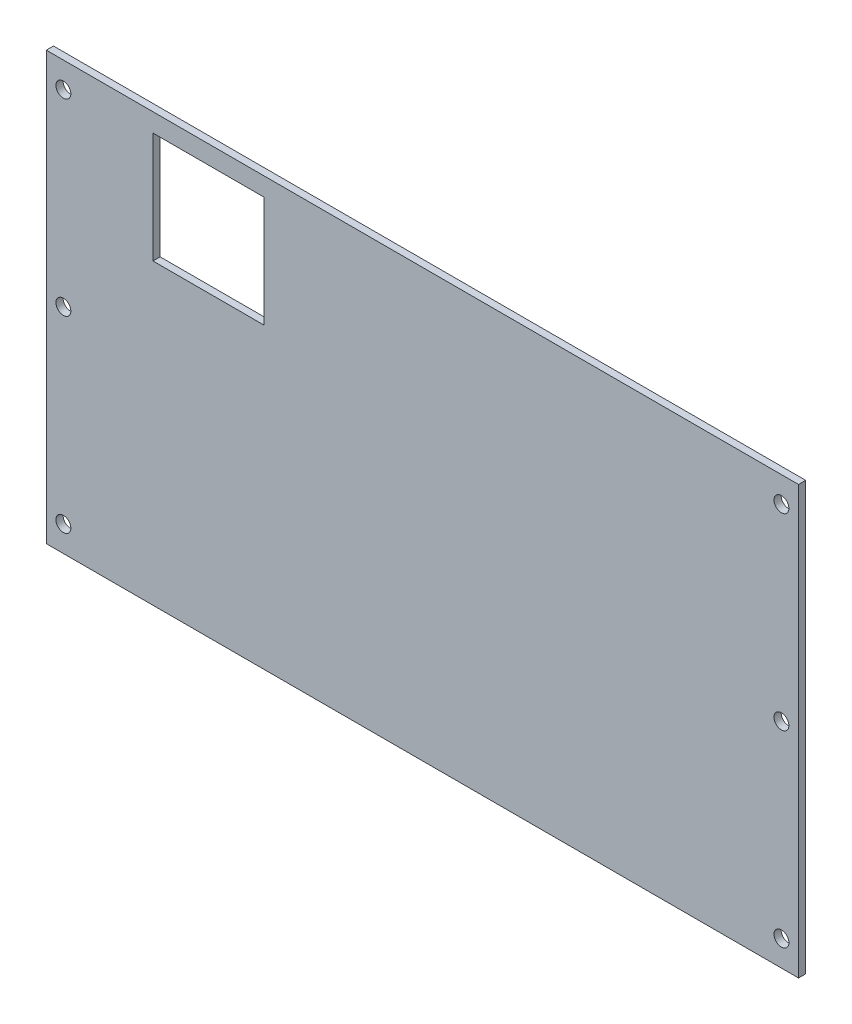
SolidWorks part; units mm, degrees
ref_plane "Front Plane" through (0, 0, 0) normal (0, 0, 1) x (1, 0, 0)
ref_plane "Top Plane" through (0, 0, 0) normal (0, 1, 0) x (1, 0, 0)
ref_plane "Right Plane" through (0, 0, 0) normal (1, 0, 0) x (0, 0, -1)
sketch "Sketch1" plane through (0, 0, 0) normal (0, 0, 1) x (1, 0, 0)
  line L1 (0, 0) -> (279.4, 0)
  line L2 (0, 0) -> (0, 158.75)
  line L3 (0, 158.75) -> (279.4, 158.75)
  line L4 (279.4, 0) -> (279.4, 158.75)
extrude "Boss-Extrude1" add sketch "Sketch1" along normal blind 2.667
sketch "Sketch2" plane through (0, 0, 0) normal (0, 0, 1) x (1, 0, 0)
  line L1 (39.624, 110.744) -> (80.772, 110.744)
  line L2 (39.624, 110.744) -> (39.624, 151.892)
  line L3 (39.624, 151.892) -> (80.772, 151.892)
  line L4 (80.772, 110.744) -> (80.772, 151.892)
extrude "Cut-Extrude1" cut sketch "Sketch2" along normal blind 47.752
sketch "Sketch3" plane through (0, 0, 0) normal (0, 0, 1) x (1, 0, 0)
  circle A0 centre (6.35, 9.525) radius 2.7686
  circle A1 centre (6.35, 79.375) radius 2.7686
  circle A2 centre (6.35, 149.225) radius 2.7686
  circle A3 centre (273.05, 9.525) radius 2.7686
  circle A4 centre (273.05, 79.375) radius 2.7686
  circle A5 centre (273.05, 149.225) radius 2.7686
extrude "Cut-Extrude2" cut sketch "Sketch3" along normal through all
